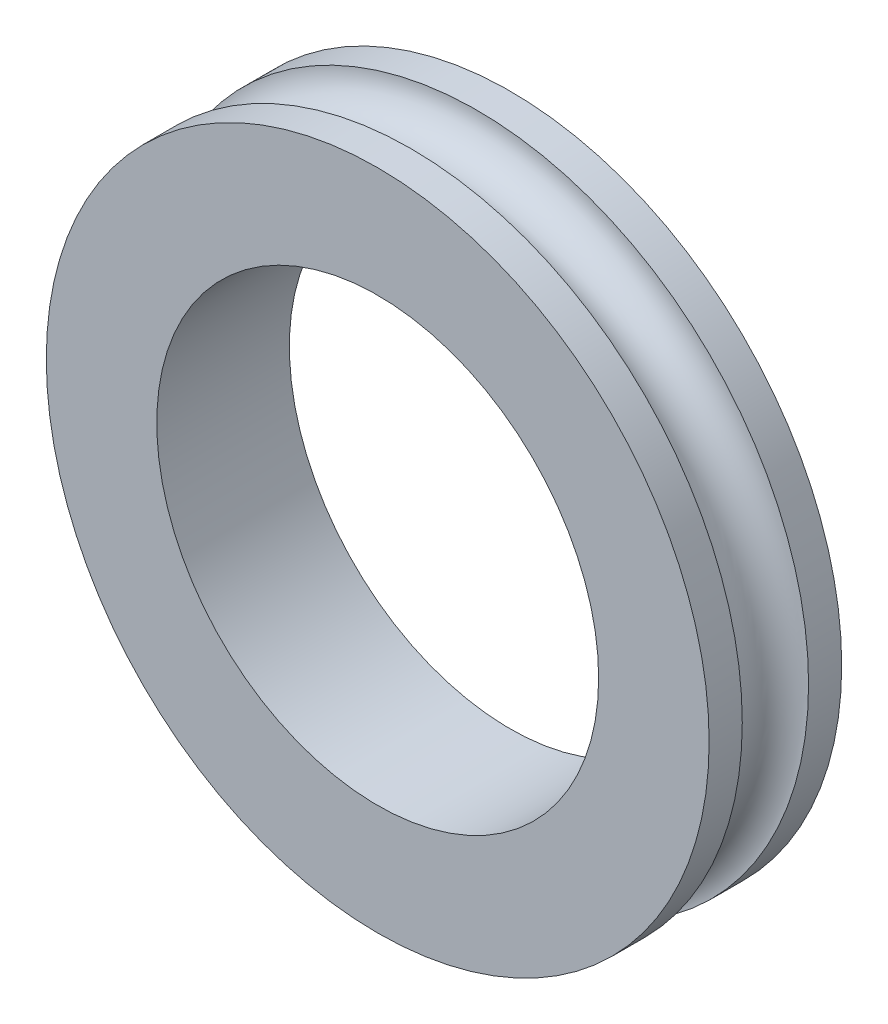
SolidWorks part; units mm, degrees
ref_plane "Alzado" through (0, 0, 0) normal (0, 0, 1) x (1, 0, 0)
ref_plane "Planta" through (0, 0, 0) normal (0, 1, 0) x (1, 0, 0)
ref_plane "Vista lateral" through (0, 0, 0) normal (1, 0, 0) x (0, 0, -1)
sketch "Croquis1" plane through (0, 0, 0) normal (0, 0, 1) x (1, 0, 0)
  circle A0 centre (0, 0) radius 7.5
  dimension "D1" = 15
extrude "Saliente-Extruir1" add sketch "Croquis1" along normal blind 3
ref_axis "Eje1" through (0, 0, 3) along (0, 0, -1)
sketch "Croquis2" plane through (0, 0, 0) normal (1, 0, 0) x (0, 0, -1)
  line L0 (0, 7.5) -> (-3, 7.5) construction
  circle A0 centre (-1.5, 7.5) radius 0.75
  dimension "D1" = 1.5
revolve "Cortar-Revolución1" cut sketch "Croquis2" angle 360 about axis through (0, 0, 3) along (0, 0, -1)
sketch "Croquis3" plane through (0, 0, 3) normal (0, 0, 1) x (1, 0, 0)
  circle A0 centre (0, 0) radius 5
  dimension "D1" = 10
extrude "Cortar-Extruir1" cut sketch "Croquis3" against normal through all
ref_plane "plano medio" through (0, 0, 1.5) normal (0, 0, 1) x (1, 0, 0)
